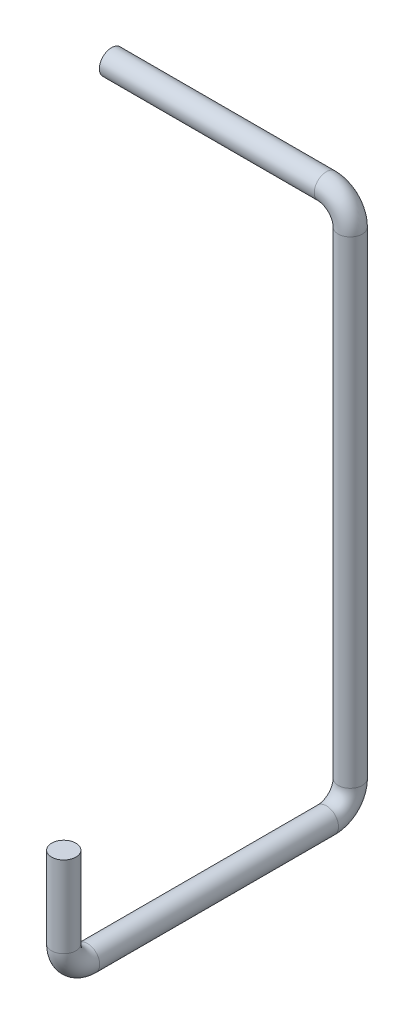
SolidWorks part; units mm, degrees
ref_plane "Alzado" through (0, 0, 0) normal (0, 0, 1) x (1, 0, 0)
ref_plane "Planta" through (0, 0, 0) normal (0, 1, 0) x (1, 0, 0)
ref_plane "Vista lateral" through (0, 0, 0) normal (1, 0, 0) x (0, 0, -1)
sketch "Croquis1" plane through (0, 0, 0) normal (0, 1, 0) x (1, 0, 0)
  circle A0 centre (0, 0) radius 12.7
  dimension "D1" = 25.4
extrude "Saliente-Extruir1" add sketch "Croquis1" against normal blind 10
sketch3d "Croquis3D1"
  line L0 (0, -10, 0) -> (0, -85, 0)
  line L1 (0, -10, 0) -> (0, 0, 0) construction
  line L2 (0, -110, -25) -> (0, -110, -275)
  line L3 (0, -85, -300) -> (0, 415, -300)
  line L4 (-25, 440, -300) -> (-250, 440, -300)
  arc A0 (0, -85, 0) -> (0, -110, -25) centre (0, -85, -25) ccw
  arc A1 (0, -110, -275) -> (0, -85, -300) centre (0, -85, -275) ccw
  arc A2 (0, 415, -300) -> (-25, 440, -300) centre (-25, 415, -300) ccw
  point P9 (0, -110, 0)
  point P10 (25, -85, -25)
  point P13 (0, -110, -300)
  point P14 (25, -85, -275)
  point P17 (0, 440, -300)
  point P18 (-25, 415, -275)
  dimension "D5" = 25
  dimension "D1" = 100
  dimension "D2" = 300
  dimension "D3" = 550
  dimension "D4" = 250
sketch "Croquis2" plane through (0, -10, 0) normal (0, -1, 0) x (1, 0, 0)
  circle A0 centre (0, 0) radius 12.7
sweep "Barrer1" add profiles "Croquis2" path "Croquis3D1"
